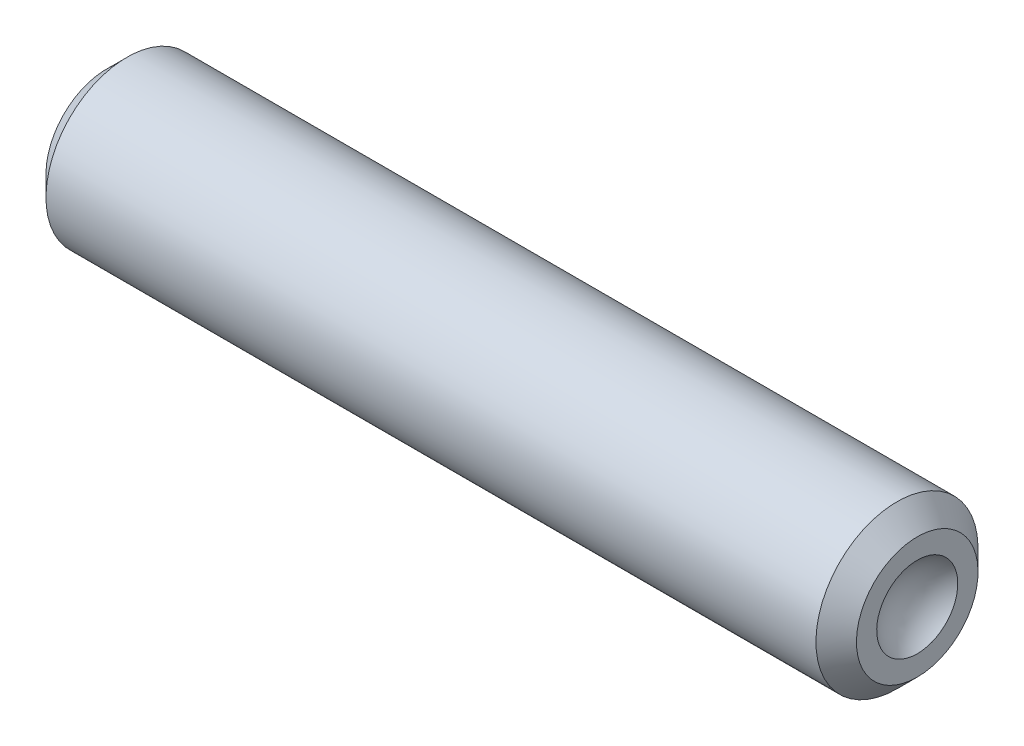
SolidWorks part; units mm, degrees
ref_plane "Front Plane" through (0, 0, 0) normal (0, 0, 1) x (1, 0, 0)
ref_plane "Top Plane" through (0, 0, 0) normal (0, 1, 0) x (1, 0, 0)
ref_plane "Right Plane" through (0, 0, 0) normal (1, 0, 0) x (0, 0, -1)
sketch "Sketch1" plane through (0, 0, 0) normal (0, 0, 1) x (1, 0, 0)
  line L0 (0, 0) -> (0, 1.5)
  line L1 (0, 1.5) -> (0.5, 2)
  line L2 (0.5, 2) -> (19.5, 2)
  line L3 (19.5, 2) -> (20, 1.5)
  line L4 (0, 0) -> (19.5, 0) construction
  line L5 (0.5, 2) -> (0.5, 1.5) construction
  line L6 (0.5, 1.5) -> (0.5, 1) construction
  line L7 (0.5, 1) -> (0.5, 0.5) construction
  line L8 (0.5, 0.5) -> (0.5, 0) construction
  line L9 (0.5, 1.5) -> (0, 1.5) construction
  line L10 (19.5, 2) -> (19.5, 0) construction
  line L11 (20, 1.5) -> (20, 1)
  line L12 (0, 0) -> (19.5, 0)
  arc A0 (19.5, 0) -> (20, 1) centre (20.75, 0) cw
  dimension "D1" = 45
  dimension "D2" = 4
  dimension "D3" = 20
  dimension "D4" = 2
revolve "Revolve1" add sketch "Sketch1" angle 360 about L12
sketch "Sketch2" plane through (0, 0, 0) normal (-1, 0, 0) x (0, 0, 1)
  line L1 (0, 1.1547) -> (-1, 0.5774)
  line L2 (-1, 0.5774) -> (-1, -0.5774)
  line L3 (-1, -0.5774) -> (0, -1.1547)
  line L4 (0, -1.1547) -> (1, -0.5774)
  line L5 (1, -0.5774) -> (1, 0.5774)
  line L6 (1, 0.5774) -> (0, 1.1547)
  circle A0 centre (0, 0) radius 1 construction
  dimension "D1" = 2
extrude "Cut-Extrude1" cut sketch "Sketch2" against normal offset from surface (18 mm away) 2 up to face at (20, -1.5, 0)
